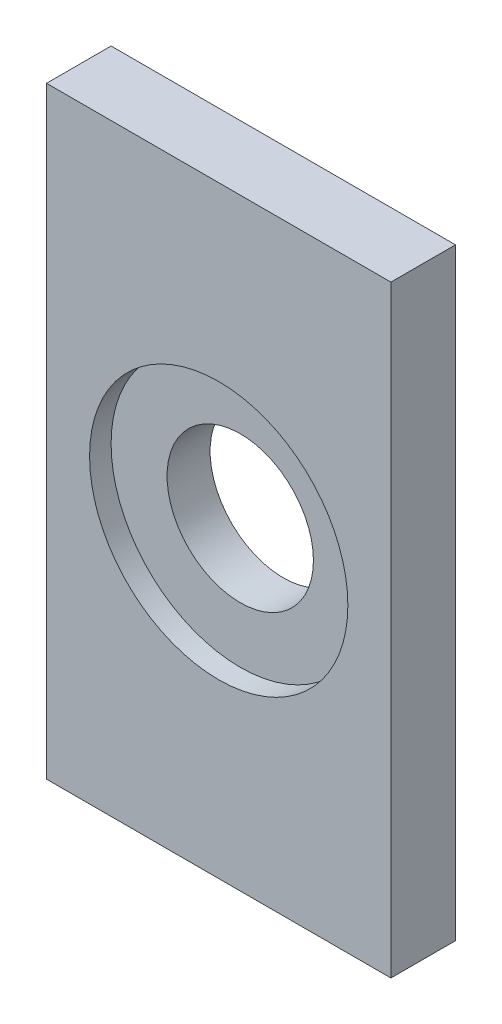
SolidWorks part; units mm, degrees
ref_plane "Front" through (0, 0, 0) normal (0, 0, 1) x (1, 0, 0)
ref_plane "Top" through (0, 0, 0) normal (0, 1, 0) x (1, 0, 0)
ref_plane "Right" through (0, 0, 0) normal (1, 0, 0) x (0, 0, -1)
sketch "Эскиз1" plane through (0, 0, 0) normal (0, 0, 1) x (1, 0, 0)
  line L1 (-4, -7) -> (4, -7)
  line L2 (-4, -7) -> (-4, 7)
  line L3 (-4, 7) -> (4, 7)
  line L4 (4, -7) -> (4, 7)
  line L5 (-4, -7) -> (4, 7) construction
  line L6 (-4, 7) -> (4, -7) construction
  circle A0 centre (0, 0) radius 1.7
  point P0 (0, 0)
  dimension "D1" = 14
  dimension "D2" = 8
extrude "Бобышка-Вытянуть1" add sketch "Эскиз1" along normal blind 1.5
sketch "Эскиз2" plane through (0, 0, 1.5) normal (0, 0, 1) x (1, 0, 0)
  circle A0 centre (0, 0) radius 3
extrude "Вырез-Вытянуть1" cut sketch "Эскиз2" against normal blind 0.5
